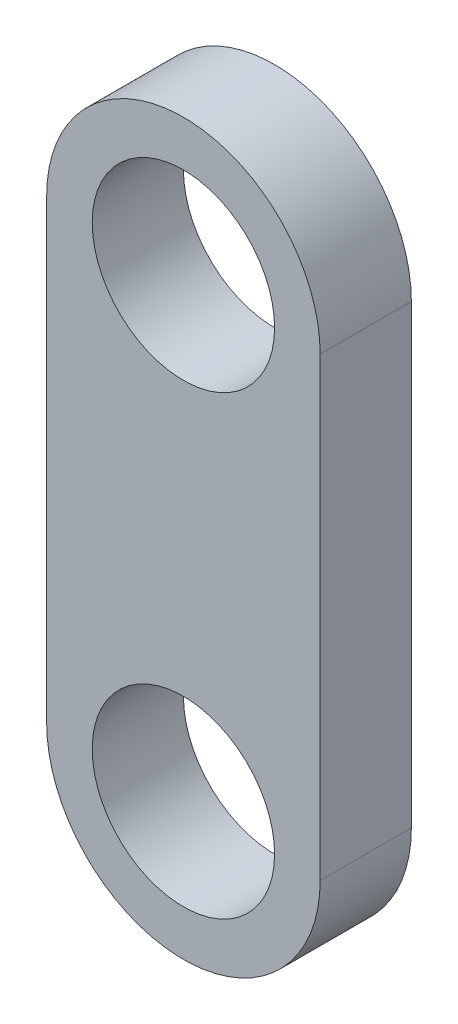
SolidWorks part; units mm, degrees
ref_plane "前视基准面" through (0, 0, 0) normal (0, 0, 1) x (1, 0, 0)
ref_plane "上视基准面" through (0, 0, 0) normal (0, 1, 0) x (1, 0, 0)
ref_plane "右视基准面" through (0, 0, 0) normal (1, 0, 0) x (0, 0, -1)
sketch "Sketch1" plane through (0, 0, 0) normal (0, 0, 1) x (1, 0, 0)
  line L2 (-3, 5) -> (-3, -5)
  line L4 (3, 5) -> (3, -5)
  line L5 (-2.1329, 7.1097) -> (2.1329, -7.1097) construction
  line L6 (-2.1329, -7.1097) -> (2.1329, 7.1097) construction
  circle A0 centre (0, 5) radius 2
  circle A1 centre (0, -5) radius 2
  arc A2 (3, 5) -> (-3, 5) centre (0, 5) ccw
  arc A3 (-3, -5) -> (3, -5) centre (0, -5) ccw
  circle A4 centre (0, 5) radius 3 construction
  circle A5 centre (0, -5) radius 3 construction
  point P0 (0, 0)
  dimension "D3" = 10
  dimension "D4" = 5
  dimension "D5" = 1
  dimension "D6" = 1
extrude "Boss-Extrude1" add sketch "Sketch1" along normal blind 2
